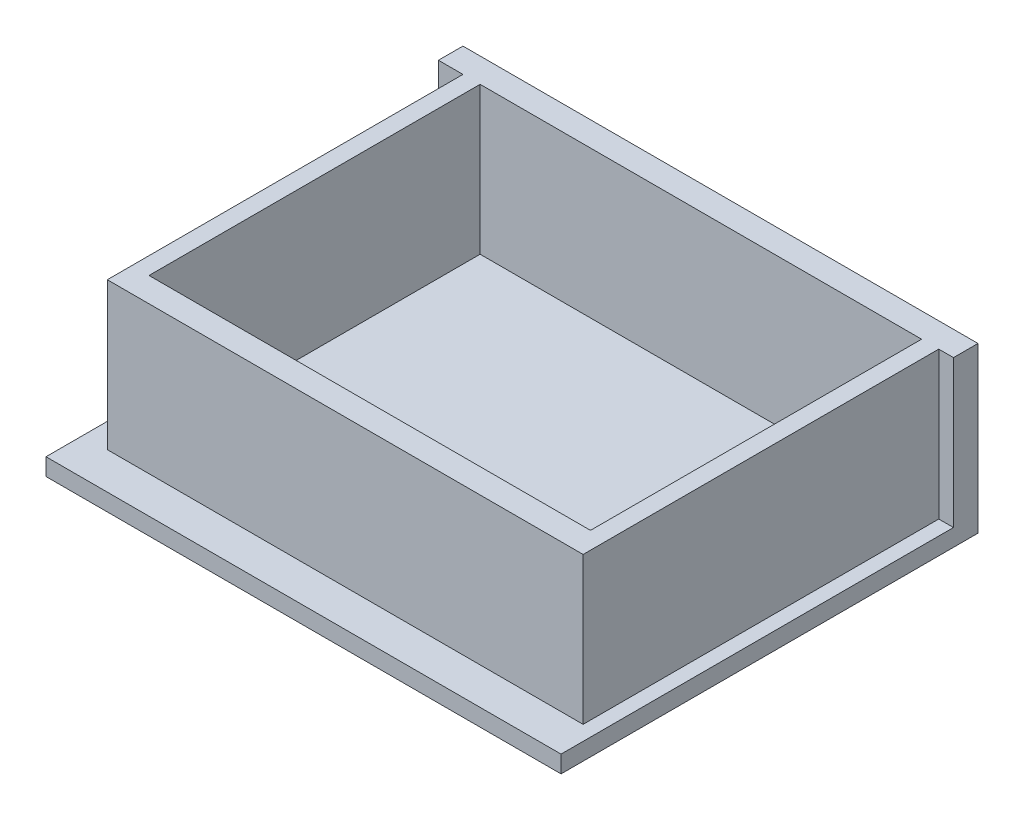
SolidWorks part; units mm, degrees
ref_plane "Front Plane" through (0, 0, 0) normal (0, 0, 1) x (1, 0, 0)
ref_plane "Top Plane" through (0, 0, 0) normal (0, 1, 0) x (1, 0, 0)
ref_plane "Right Plane" through (0, 0, 0) normal (1, 0, 0) x (0, 0, -1)
sketch "Sketch1" plane through (0, 0, 0) normal (0, 1, 0) x (1, 0, 0)
  line L1 (0, 0) -> (210, 0)
  line L2 (0, 0) -> (0, 170)
  line L3 (0, 170) -> (210, 170)
  line L4 (210, 0) -> (210, 170)
  dimension "D1" = 170
  dimension "D2" = 210
extrude "Boss-Extrude1" add sketch "Sketch1" along normal blind 7
sketch "Sketch2" plane through (0, 7, 0) normal (0, 1, 0) x (1, 0, 0)
  line L0 (210, 0) -> (210, 170) construction
  line L1 (0, 170) -> (210, 170)
  line L2 (0, 170) -> (0, 160)
  line L3 (0, 160) -> (10, 160)
  line L4 (210, 170) -> (210, 160)
  line L5 (0, 170) -> (0, 0) construction
  line L6 (204, 15) -> (10, 15)
  line L7 (204, 15) -> (204, 25)
  line L8 (197, 25) -> (17, 25)
  line L9 (10, 15) -> (10, 25)
  line L10 (17, 160) -> (197, 160)
  line L11 (17, 160) -> (17, 25)
  line L13 (10, 160) -> (10, 20.5004)
  line L15 (197, 25) -> (197, 160)
  line L17 (204, 18.1994) -> (204, 160)
  line L18 (0, 0) -> (210, 0) construction
  line L19 (204, 160) -> (210, 160)
  dimension "D1" = 7
  dimension "D2" = 7
  dimension "D3" = 10
  dimension "D4" = 10
  dimension "D5" = 10
  dimension "D6" = 6
  dimension "D7" = 15
extrude "Boss-Extrude2" add sketch "Sketch2" along normal blind 60
